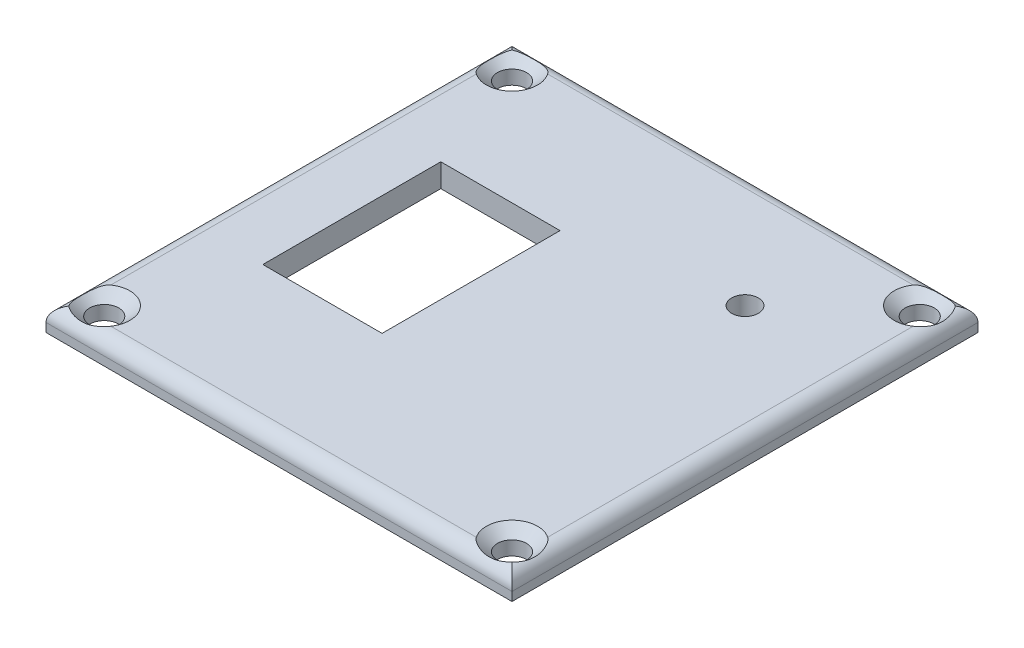
SolidWorks part; units mm, degrees
material "PET"
ref_plane "Front Plane" through (0, 0, 0) normal (0, 0, 1) x (1, 0, 0)
ref_plane "Top Plane" through (0, 0, 0) normal (0, 1, 0) x (1, 0, 0)
ref_plane "Right Plane" through (0, 0, 0) normal (1, 0, 0) x (0, 0, -1)
sketch "Sketch1" plane through (0, 0, 0) normal (0, 1, 0) x (1, 0, 0)
  line L0 (47.625, 3.175) -> (50.8, 3.175) construction
  line L1 (0, 0) -> (50.8, 0)
  line L2 (0, 0) -> (0, 50.8)
  line L3 (0, 50.8) -> (50.8, 50.8)
  line L4 (50.8, 0) -> (50.8, 50.8)
  line L5 (3.175, 3.175) -> (0, 3.175) construction
  line L6 (3.175, 3.175) -> (3.175, 0) construction
  line L7 (3.175, 47.625) -> (3.175, 50.8) construction
  circle A0 centre (3.175, 47.625) radius 2.54 construction
  circle A1 centre (47.625, 47.625) radius 2.54 construction
  circle A2 centre (47.625, 3.175) radius 2.54 construction
  circle A3 centre (3.175, 3.175) radius 2.54 construction
  dimension "D3" = 44.45
  dimension "D5" = 5.08
  dimension "D1" = 50.8
  dimension "D2" = 50.8
  dimension "D4" = 44.45
extrude "Boss-Extrude1" add sketch "Sketch1" along normal blind 2.54
fillet "Fillet1" radius 1.5875 4 edges at (25.4, 2.54, -50.8) (50.8, 2.54, -25.4) (25.4, 2.54, 0) (0, 2.54, -25.4)
hole_wizard "CSK for M3 Flat Head Machine Screw1" positions "Sketch2" profile "Sketch3" countersink size "M3" standard "ANSI Metric" end condition through all
sketch "Sketch2" plane through (0, 2.54, 0) normal (0, 1, 0) x (1, 0, 0)
  point P0 (3.175, 47.625)
  point P3 (47.625, 47.625)
  point P6 (47.625, 3.175)
  point P9 (3.175, 3.175)
sketch "Sketch3" plane through (3.175, 2.54, -47.625) normal (1, 0, 0) x (0, 0, 1)
  line L0 (0, 0) -> (0, 2.54)
  line L1 (0, 2.54) -> (1.5875, 2.54)
  line L2 (1.5875, 2.54) -> (1.5875, 1.0124)
  line L3 (1.5875, 1.0124) -> (2.794, 0)
  line L5 (2.794, 0) -> (0, 0)
  line L6 (-1.5875, 1.0124) -> (-2.794, 0) construction
  line L11 (0, -6.35) -> (0, 107.95) construction
  dimension "Thru Hole Dia." = 3.175
  dimension "Thru Hole Depth" = 2.54
  dimension "Near C'Sink Dia." = 5.588
  dimension "Near C'Sink Angle" = 100
sketch "Sketch4" plane through (0, 2.54, 0) normal (0, 1, 0) x (1, 0, 0)
  line L0 (7.9375, 25.4) -> (1.5875, 25.4)
  line L1 (7.9375, 35.1) -> (20.9375, 35.1)
  line L2 (7.9375, 35.1) -> (7.9375, 15.7)
  line L3 (7.9375, 15.7) -> (20.9375, 15.7)
  line L4 (20.9375, 35.1) -> (20.9375, 15.7)
  line L5 (1.5875, 45.3258) -> (1.5875, 5.4742) construction
  dimension "D1" = 19.4
  dimension "D2" = 13
  dimension "D3" = 6.35
extrude "Cut-Extrude1" cut sketch "Sketch4" against normal through all contours L4 L1 L2 L3
sketch "Sketch5" plane through (0, 2.54, 0) normal (0, 1, 0) x (1, 0, 0)
  line L0 (50.8, 0) -> (50.8, 50.8) construction
  line L1 (0, 50.8) -> (50.8, 50.8) construction
  circle A0 centre (38.1, 38.1) radius 1.4605
  point P2 (0, 0)
  dimension "D1" = 2.921
  dimension "D2" = 12.7
  dimension "D3" = 12.7
extrude "Cut-Extrude2" cut sketch "Sketch5" against normal through all
